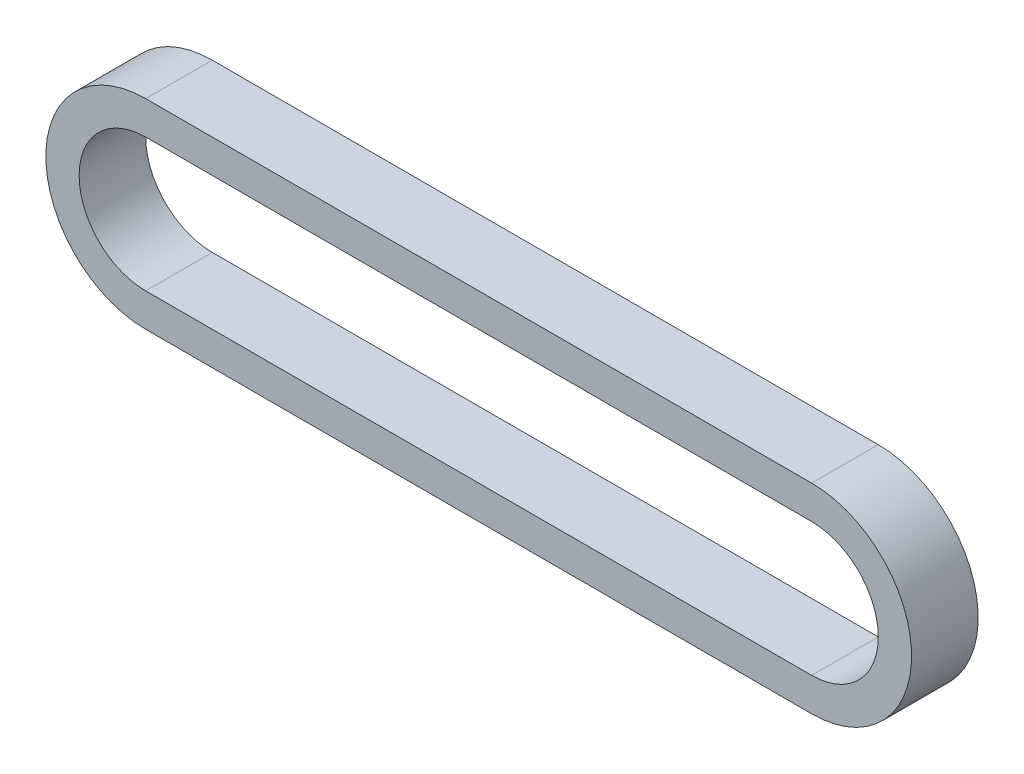
SolidWorks part; units mm, degrees
ref_plane "前视基准面" through (0, 0, 0) normal (0, 0, 1) x (1, 0, 0)
ref_plane "上视基准面" through (0, 0, 0) normal (0, 1, 0) x (1, 0, 0)
ref_plane "右视基准面" through (0, 0, 0) normal (1, 0, 0) x (0, 0, -1)
other "Configuration Table"
sketch "草图1" plane through (0, 0, 0) normal (0, 0, 1) x (1, 0, 0)
  line L0 (-5.0274, 4.8513) -> (4.9726, 4.8513)
  line L1 (-5.0274, 2.8513) -> (4.9726, 2.8513)
  line L2 (-5.0274, 5.3513) -> (4.9726, 5.3513)
  line L3 (-5.0274, 2.3513) -> (4.9726, 2.3513)
  arc A0 (-5.0274, 4.8513) -> (-5.0274, 2.8513) centre (-5.0274, 3.8513) ccw
  arc A1 (4.9726, 2.8513) -> (4.9726, 4.8513) centre (4.9726, 3.8513) ccw
  arc A2 (4.9726, 2.3513) -> (4.9726, 5.3513) centre (4.9726, 3.8513) ccw
  arc A3 (-5.0274, 5.3513) -> (-5.0274, 2.3513) centre (-5.0274, 3.8513) ccw
  point P8 (0, 0)
  point P9 (4.9726, 4.8513)
  dimension "D1" = 2
  dimension "D2" = 2
  dimension "D3" = 0.5
  dimension "D4" = 10
extrude "凸台-拉伸1" add sketch "草图1" along normal mid plane 1
